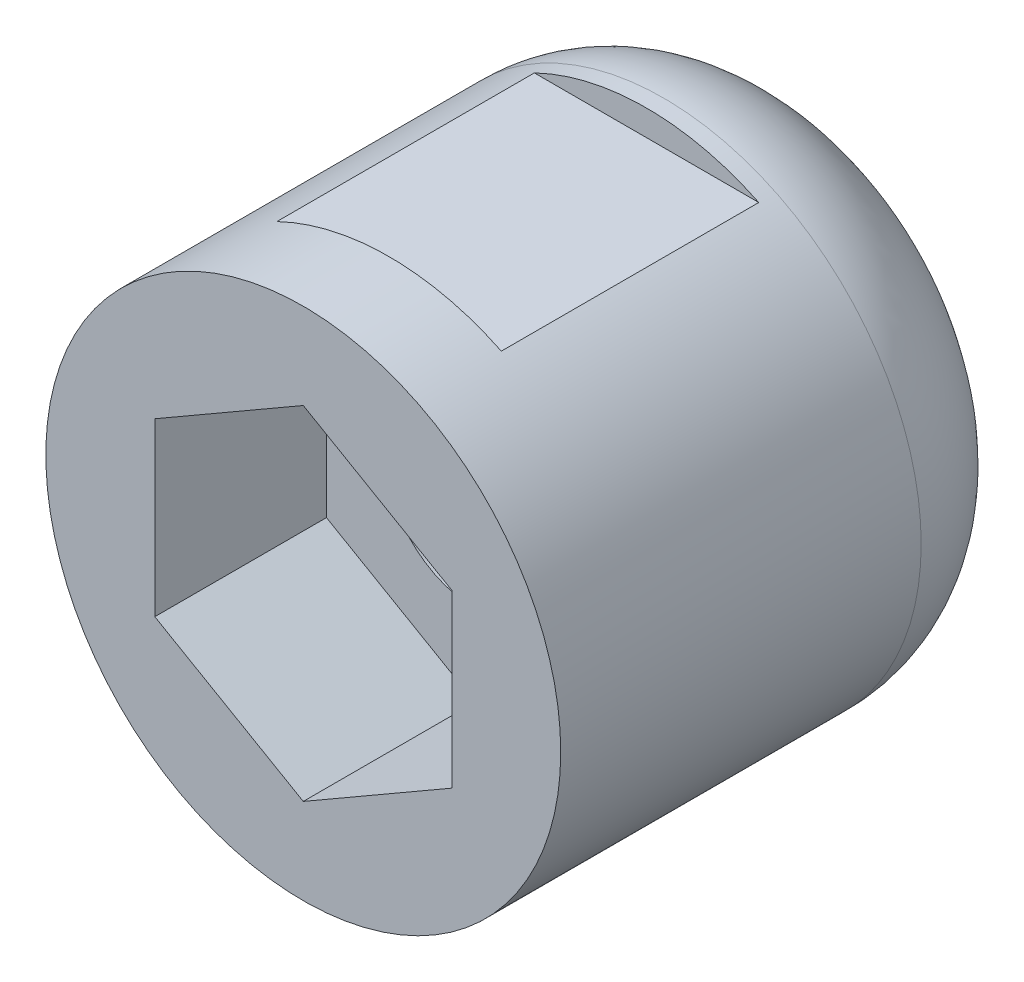
SolidWorks part; units mm, degrees
ref_plane "前视基准面" through (0, 0, 0) normal (0, 0, 1) x (1, 0, 0)
ref_plane "上视基准面" through (0, 0, 0) normal (0, 1, 0) x (1, 0, 0)
ref_plane "右视基准面" through (0, 0, 0) normal (1, 0, 0) x (0, 0, -1)
sketch "草图1" plane through (0, 0, 0) normal (0, 0, 1) x (1, 0, 0)
  circle A0 centre (0, 0) radius 15
  circle A1 centre (0, 0) radius 5.25
  dimension "D1" = 10.5
  dimension "D2" = 30
extrude "凸台-拉伸1" add sketch "草图1" along normal mid plane 29
sketch "草图2" plane through (0, 0, 14.5) normal (0, 0, 1) x (1, 0, 0)
  line L1 (0, 9.9882) -> (-8.65, 4.9941)
  line L2 (-8.65, 4.9941) -> (-8.65, -4.9941)
  line L3 (-8.65, -4.9941) -> (0, -9.9882)
  line L4 (0, -9.9882) -> (8.65, -4.9941)
  line L5 (8.65, -4.9941) -> (8.65, 4.9941)
  line L6 (8.65, 4.9941) -> (0, 9.9882)
  circle A0 centre (0, 0) radius 8.65 construction
  dimension "D1" = 17.3
extrude "切除-拉伸1" cut sketch "草图2" against normal blind 10
fillet "圆角2" radius 8 1 edges at (15, 0, -14.5)
sketch "草图3" plane through (0, 0, 0) normal (1, 0, 0) x (0, 0, -1)
  line L0 (-9.5, 15) -> (-9.5, 13.5)
  line L1 (6.5, 15) -> (-14.5, 15) construction
  line L2 (-9.5, 13.5) -> (5.5, 13.5)
  line L3 (5.5, 13.5) -> (5.5, 15)
  line L4 (5.5, 15) -> (-9.5, 15)
  line L5 (-14.5, 0) -> (14.5, 0) construction
  line L6 (-14.5, 15) -> (-14.5, -15) construction
  line L7 (14.5, -7) -> (14.5, 7) construction
  line L8 (5.5, -13.5) -> (5.5, -15)
  line L9 (5.5, -15) -> (-9.5, -15)
  line L10 (-9.5, -15) -> (-9.5, -13.5)
  line L11 (-9.5, -13.5) -> (5.5, -13.5)
  dimension "D1" = 27
  dimension "D2" = 5
  dimension "D3" = 15
extrude "切除-拉伸2" cut sketch "草图3" against normal through all both and the other way through all
